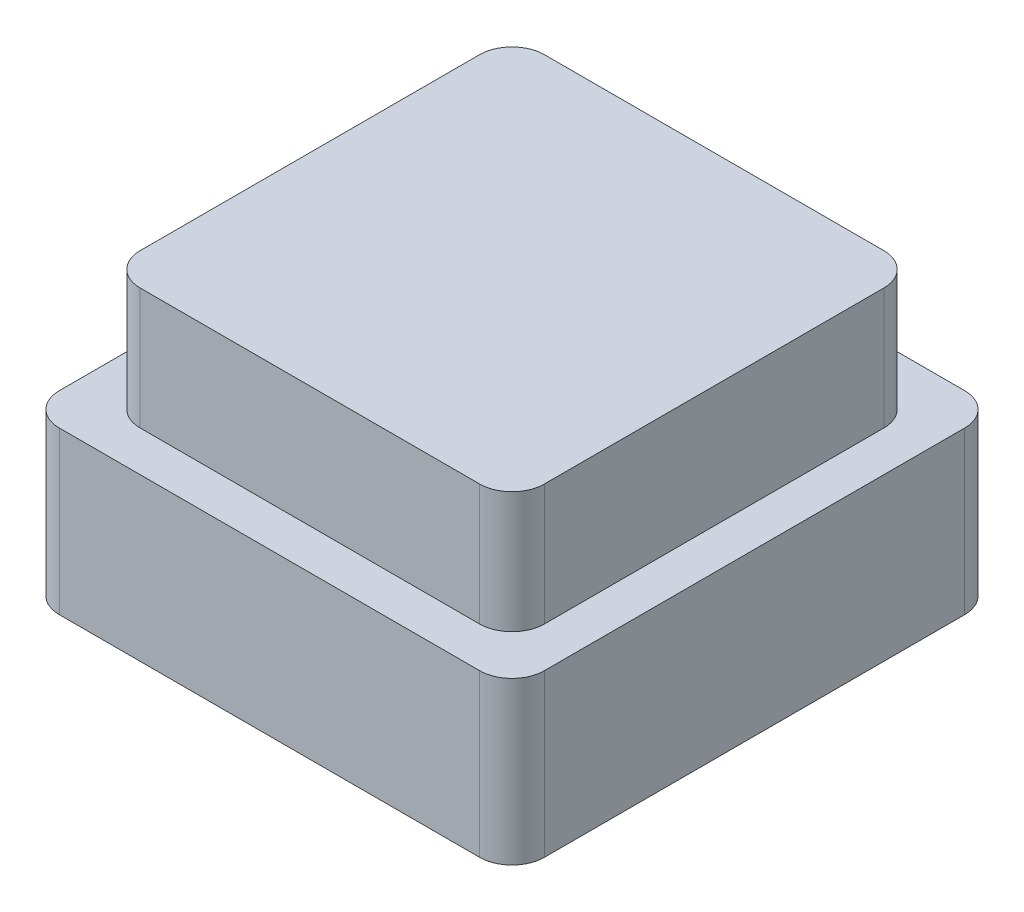
SolidWorks part; units mm, degrees
ref_plane "Front Plane" through (0, 0, 0) normal (0, 0, 1) x (1, 0, 0)
ref_plane "Top Plane" through (0, 0, 0) normal (0, 1, 0) x (1, 0, 0)
ref_plane "Right Plane" through (0, 0, 0) normal (1, 0, 0) x (0, 0, -1)
sketch "Sketch1" plane through (0, 0, 0) normal (0, 1, 0) x (1, 0, 0)
  line L1 (-19.05, -19.05) -> (19.05, -19.05)
  line L2 (-19.05, -19.05) -> (-19.05, 19.05)
  line L3 (-19.05, 19.05) -> (19.05, 19.05)
  line L4 (19.05, -19.05) -> (19.05, 19.05)
  line L5 (-19.05, -19.05) -> (19.05, 19.05) construction
  line L6 (-19.05, 19.05) -> (19.05, -19.05) construction
  point P0 (0, 0)
  dimension "D1" = 38.1
  dimension "D2" = 38.1
extrude "Boss-Extrude1" add sketch "Sketch1" along normal blind 12.7
fillet "Fillet1" radius 2.54 4 edges at (19.05, 6.35, -19.05) (-19.05, 6.35, -19.05) (-19.05, 6.35, 19.05) (19.05, 6.35, 19.05)
shell "Shell1" thickness 3.175
fillet "Fillet2" radius 2.54 4 edges at (15.875, 7.9375, -15.875) (-15.875, 7.9375, -15.875) (15.875, 7.9375, 15.875) (-15.875, 7.9375, 15.875)
sketch "Sketch2" plane through (0, 3.175, 0) normal (0, 1, 0) x (1, 0, 0)
  line L4 (15.875, -13.335) -> (15.875, 13.335)
  line L5 (13.335, 15.875) -> (-13.335, 15.875)
  line L6 (-15.875, 13.335) -> (-15.875, -13.335)
  line L7 (-13.335, -15.875) -> (13.335, -15.875)
  line L8 (15.875, -13.335) -> (15.875, 13.335)
  line L9 (13.335, 15.875) -> (-13.335, 15.875)
  line L10 (-15.875, 13.335) -> (-15.875, -13.335)
  line L11 (-13.335, -15.875) -> (13.335, -15.875)
  arc A4 (15.875, 13.335) -> (13.335, 15.875) centre (13.335, 13.335) ccw
  arc A5 (-13.335, 15.875) -> (-15.875, 13.335) centre (-13.335, 13.335) ccw
  arc A6 (-15.875, -13.335) -> (-13.335, -15.875) centre (-13.335, -13.335) ccw
  arc A7 (13.335, -15.875) -> (15.875, -13.335) centre (13.335, -13.335) ccw
  arc A8 (15.875, 13.335) -> (13.335, 15.875) centre (13.335, 13.335) ccw
  arc A9 (-13.335, 15.875) -> (-15.875, 13.335) centre (-13.335, 13.335) ccw
  arc A10 (-15.875, -13.335) -> (-13.335, -15.875) centre (-13.335, -13.335) ccw
  arc A11 (13.335, -15.875) -> (15.875, -13.335) centre (13.335, -13.335) ccw
  dimension "D1" = 0
extrude "Boss-Extrude2" add sketch "Sketch2" along normal blind 19.05
